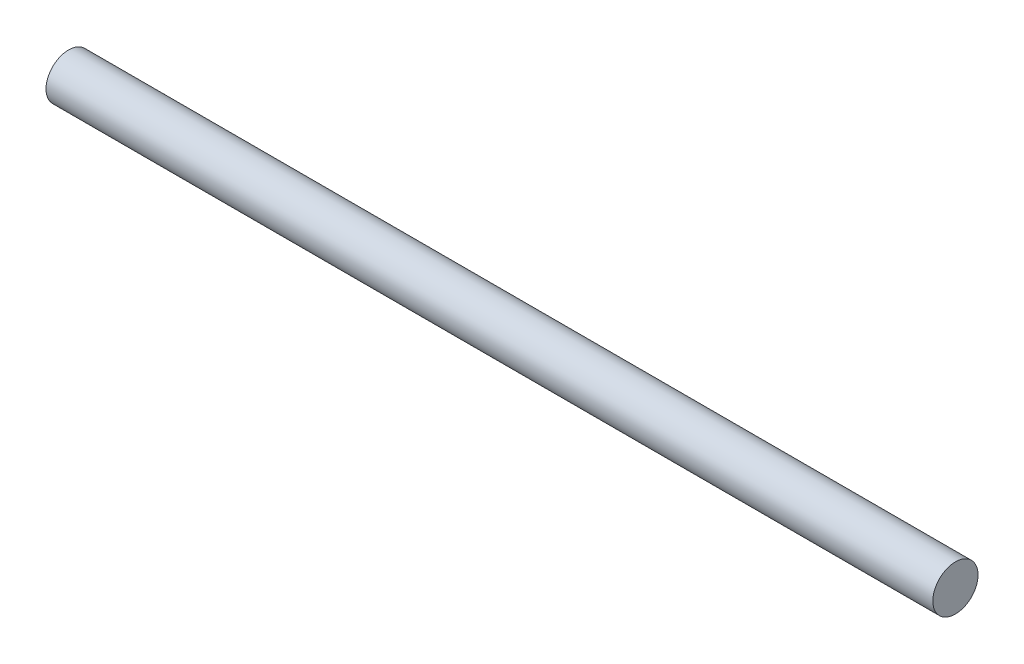
SolidWorks part; units mm, degrees
ref_plane "Front" through (0, 0, 0) normal (0, 0, 1) x (1, 0, 0)
ref_plane "Top" through (0, 0, 0) normal (0, 1, 0) x (1, 0, 0)
ref_plane "Right" through (0, 0, 0) normal (1, 0, 0) x (0, 0, -1)
sketch "Эскиз1" plane through (0, 0, 0) normal (0, 0, 1) x (1, 0, 0)
  line L0 (-19.6958, 0) -> (19.6958, 0) construction
  line L1 (-24.5, 0) -> (24.5, 0)
  line L2 (-24.5, 1.25) -> (24.5, 1.25)
  line L3 (-24.5, 1.25) -> (-24.5, -1.25)
  line L4 (-24.5, -1.25) -> (24.5, -1.25)
  line L5 (24.5, 1.25) -> (24.5, -1.25)
  line L6 (-24.5, 1.25) -> (24.5, -1.25) construction
  line L7 (-24.5, -1.25) -> (24.5, 1.25) construction
  point P3 (0, 0)
  dimension "D1" = 49
  dimension "D2" = 2.5
revolve "Повернуть1" add sketch "Эскиз1" angle 360 about L1
